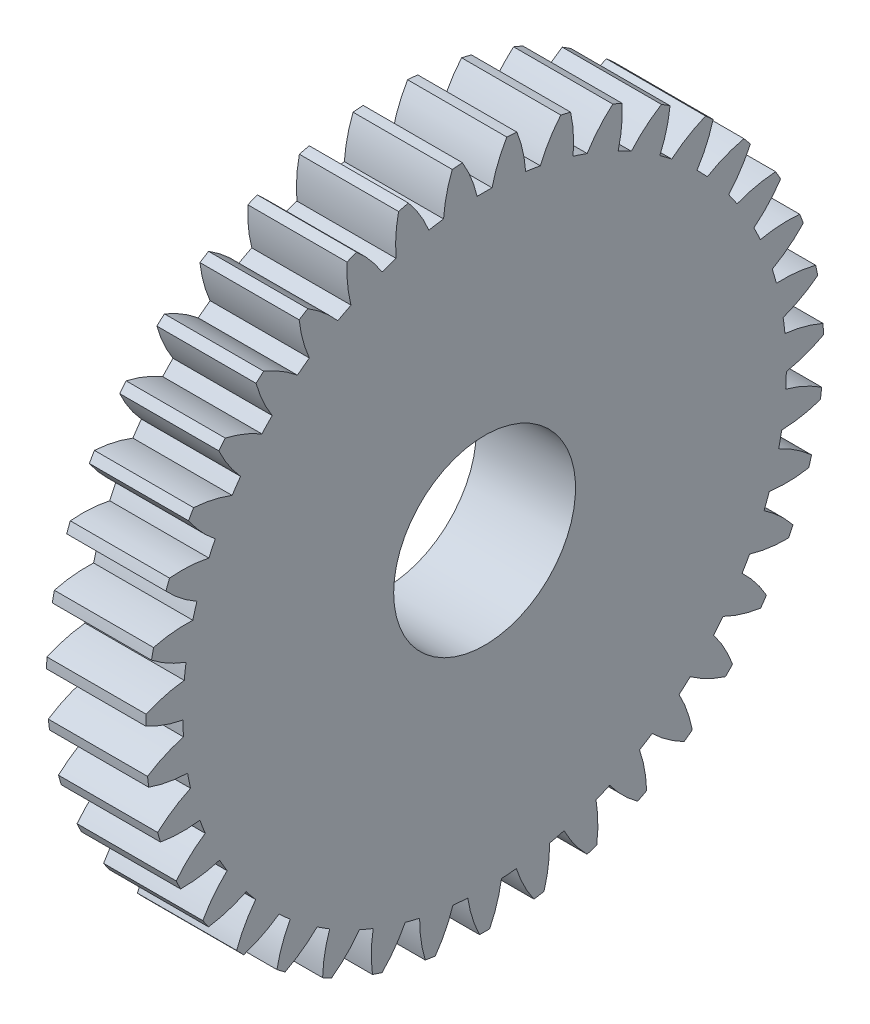
SolidWorks part; units mm, degrees
ref_plane "Plane1" through (0, 0, 0) normal (0, 0, 1) x (1, 0, 0)
ref_plane "Plane2" through (0, 0, 0) normal (0, 1, 0) x (1, 0, 0)
ref_plane "Plane3" through (0, 0, 0) normal (1, 0, 0) x (0, 0, -1)
other "Configuration Table"
sketch "HoldingSke" plane through (0, 0, 0) normal (0, 1, 0) x (1, 0, 0)
  line L0 (0, 0) -> (0.7771, -0.6293)
  line L1 (-15, 0) -> (100, 0) construction
  line L2 (0, 0) -> (-2.1039, 2.3779)
  line L3 (0, 0) -> (-11.863, 4.5341)
  line L4 (0, 0) -> (6.7114, 5.4348)
  line L5 (0, 0) -> (-46.8476, -17.4728)
  line L6 (0, 0) -> (-4.9738, -3.3558)
  line L7 (-2.1039, 2.3779) -> (8.6586, 51.2059)
  line L8 (-76.2, 54.61) -> (-74.4, 54.61)
  line L9 (-71.009, 38.7566) -> (-53.1078, 45.2721)
  line L10 (-76.2, 71.12) -> (104.1128, 71.12)
  line L11 (0, 0) -> (-6, 0)
  line L12 (-76.2, 101.6) -> (-76.162, 101.6)
  line L13 (24.9733, 27.94) -> (52.9518, 28.4284)
  line L14 (24.9733, 27.94) -> (24.9743, 27.94)
  line L15 (24.9733, 27.94) -> (100.4006, 29.5858)
  line L16 (-63.627, -1) -> (-12.827, -1)
  circle A0 centre (0, 0) radius 5.5
  circle A1 centre (0, 0) radius 18.249
  circle A2 centre (0, 0) radius 37.5
  circle A3 centre (0, 0) radius 5.5
  dimension "MHD" = 36.498
  dimension "Hub_dia" = 75
  dimension "Bore" = 11
  dimension "MBD" = 11
  dimension "Num_teeth" = 39
  dimension "Pitch" = 1
  dimension "Overall_len" = 50
  dimension "Show_teeth" = 39
  dimension "Thickness" = 6
  dimension "OAL" = 50.0001
  dimension "T_dim" = 1.8
  dimension "Ap" = 20
  dimension "H" = 19.05
  dimension "Pitch_radius" = 180.3128
  dimension "Width" = 6
  dimension "Backlash" = 0.038
  dimension "Addendum_fac" = 1
  dimension "Dedendum_fac" = 1.25
  dimension "Clearance_fac" = 0.25
  dimension "Dedendum_add" = 0.001
  dimension "Module" = 1
sketch "BasProSke" plane through (0, 0, 0) normal (0, 1, 0) x (1, 0, 0)
  line L0 (-10, 0) -> (60, 0) construction
  line L1 (0, 0) -> (0, 20.5)
  line L2 (0, 0) -> (6, 0)
  line L3 (6, 0) -> (6, 20.5)
  line L4 (6, 20.5) -> (0, 20.5)
  dimension "Thickness" = 6
  dimension "Diameter" = 41
revolve "Base-Revolve" add sketch "BasProSke" angle 360 about L0
sketch "TooCutSke" plane through (0, 0, 0) normal (1, 0, 0) x (0, 0, -1)
  line L1 (0, 0) -> (0, 107) construction
  line L2 (0, 0) -> (-0.8517, 19.4814) construction
  line L3 (0, 0) -> (-3.1361, 38.8471) construction
  line L4 (-0.8517, 19.4814) -> (-1.568, 19.4236) construction
  arc A0 (0.4501, 18.2434) -> (-0.4501, 18.2434) centre (0, 0) ccw
  arc A1 (1.358, 20.4804) -> (-1.358, 20.4804) centre (0, 0) ccw
  circle A2 centre (0, 0) radius 19.5 construction
  circle A3 centre (0, 0) radius 18.324 construction
  arc A4 (-0.4501, 18.2434) -> (-1.358, 20.4804) centre (-8.0443, 16.4638) ccw
  arc A5 (1.358, 20.4804) -> (0.4501, 18.2434) centre (8.0443, 16.4638) ccw
  dimension "Root_dia" = 36.498
  dimension "Overcut_dia" = 41.0508
  dimension "Pitch_dia" = 39
  dimension "Base_dia" = 36.648
  dimension "Flank_rad" = 7.8
  dimension "Half_ang" = 4.615
  dimension "Half_CT" = 0.7187
extrude "ToothCut" cut sketch "TooCutSke" along normal through all
fillet "Breaks" [suppressed] radius 0.02
fillet "RootFillets" [suppressed] radius 0.251
pattern_circular "TeethCuts" count 39 every 9.231 about axis through (-10, 0, 0) along (1, 0, 0) of "ToothCut", "RootFillets", "Breaks"
sketch "HubNeaOneSke" plane through (0, 0, 0) normal (-1, 0, 0) x (0, 0, 1)
  circle A0 centre (0, 0) radius 18.249
  dimension "Diameter" = 36.498
extrude "HubNearOne" [suppressed] add sketch "HubNeaOneSke" along normal blind 44.0001
sketch "HubNeaBotSke" plane through (0, 0, 0) normal (-1, 0, 0) x (0, 0, 1)
  circle A0 centre (0, 0) radius 18.249
  dimension "Diameter" = 36.498
extrude "HubNearBoth" [suppressed] add sketch "HubNeaBotSke" along normal blind 22
ref_plane "FarPln" through (6, 0, 0) normal (1, 0, 0) x (0, 0, -1)
sketch "HubFarSke" plane through (6, 0, 0) normal (1, 0, 0) x (0, 0, -1)
  circle A0 centre (0, 0) radius 18.249
  dimension "Diameter" = 36.498
extrude "HubFar" [suppressed] add sketch "HubFarSke" along normal blind 22
sketch "BorSke" plane through (0, 0, 0) normal (1, 0, 0) x (0, 0, -1)
  circle A0 centre (0, 0) radius 5.5
  dimension "Diameter" = 11
extrude "Bore" cut sketch "BorSke" along normal mid plane 100.0001
sketch "KeySke" plane through (0, 0, 0) normal (1, 0, 0) x (0, 0, -1)
  line L0 (-2, 0) -> (-2, 7.3)
  line L1 (-2, 7.3) -> (2, 7.3)
  line L2 (2, 7.3) -> (2, 0)
  line L3 (0, 0) -> (0, 34) construction
  line L4 (-2, 0) -> (2, 0)
  dimension "Offset" = 7.3
  dimension "Width" = 4
extrude "Keyway" [suppressed] cut sketch "KeySke" along normal mid plane 100.0001
pattern_circular "Keyway2" [suppressed] count 2 every 90 about axis through (-10, 0, 0) along (1, 0, 0)
equation "' \"Module@HoldingSke\" = 6.35"
equation "' \"Num_teeth@HoldingSke\" = 12"
equation "' \"Ap@HoldingSke\" =  20"
equation "' \"Ap@HoldingSke\" = 20"
equation "' \"Width@HoldingSke\" = 0.5 * 25.4"
equation "' \"Hub_dia@HoldingSke\"= 1 * 25.4"
equation "' \"Hub_dia@HoldingSke\" = 1 * 25.4"
equation "' \"Overall_len@HoldingSke\" = 1.0 * 25.4"
equation "' \"Bore@HoldingSke\" = 0.75 * 25.4"
equation "' \"T_dim@HoldingSke\" = 0.1 * 25.4"
equation "' \"Width@KeySke\" = 0.25 * 25.4"
equation "' \"Show_teeth@HoldingSke\" = 13"
equation "' \"Backlash@HoldingSke\" = 0.009 * 25.4"
equation "' \"Addendum_fac@HoldingSke\" = 1.0"
equation "' \"Dedendum_fac@HoldingSke\" = 1.25"
equation "' \"Dedendum_add@HoldingSke\" = 0.00005 * 25.4"
equation "' \"Clearance_fac@HoldingSke\" = 0.25"
equation "\"Pitch@HoldingSke\" = 1 / \"Module@HoldingSke\""
equation "\"Overcut_dia@TooCutSke\" = (\"Num_teeth@HoldingSke\" + 2 * \"Addendum_fac@HoldingSke\") / \"Pitch@HoldingSke\" + 0.002 * 25.4"
equation "\"Pitch_dia@TooCutSke\" = \"Num_teeth@HoldingSke\" / \"Pitch@HoldingSke\""
equation "\"Base_dia@TooCutSke\" = \"Num_teeth@HoldingSke\" / \"Pitch@HoldingSke\" * cos((\"Ap@HoldingSke\"  * 3.14159265 / 180))"
equation "\"Root_dia@TooCutSke\" = (\"Num_teeth@HoldingSke\" + 2) / \"Pitch@HoldingSke\" - 2 * (\"Addendum_fac@HoldingSke\" + \"Dedendum_fac@HoldingSke\") / \"Pitch@HoldingSke\" - \"Dedendum_add@HoldingSke\" * 2"
equation "\"Half_ang@TooCutSke\" = 180 / \"Num_teeth@HoldingSke\""
equation "\"Half_CT@TooCutSke\" = \"Num_teeth@HoldingSke\" / \"Pitch@HoldingSke\" * sin((3.14159265 / 2 / \"Num_teeth@HoldingSke\")) / 2 - 7 * \"Backlash@HoldingSke\" / 4"
equation "\"Flank_rad@TooCutSke\" = \"Num_teeth@HoldingSke\" / \"Pitch@HoldingSke\" / 5"
equation "\"Radius@RootFillets\" = \"Clearance_fac@HoldingSke\" / \"Pitch@HoldingSke\" + \"Dedendum_add@HoldingSke\""
equation "\"Break_rad@Breaks\" = 0.02 / \"Pitch@HoldingSke\""
equation "\"Thickness@HoldingSke\" = \"Width@HoldingSke\""
equation "\"OAL@HoldingSke\" = \"Thickness@HoldingSke\""
equation "\"MHD@HoldingSke\" = (\"Num_teeth@HoldingSke\" + 2) / \"Pitch@HoldingSke\" - 2 * (\"Addendum_fac@HoldingSke\" + \"Dedendum_fac@HoldingSke\")  / \"Pitch@HoldingSke\" - \"Dedendum_add@HoldingSke\" * 2"
equation "\"MBD@HoldingSke\" = (\"Num_teeth@HoldingSke\" + 2) / \"Pitch@HoldingSke\" - 2 * (\"Addendum_fac@HoldingSke\" + \"Dedendum_fac@HoldingSke\")  / \"Pitch@HoldingSke\" - \"Dedendum_add@HoldingSke\" * 2 - 0.002 * 25.4"
equation "\"MHD@HoldingSke\" = ((sgn( \"MHD@HoldingSke\" - \"Hub_dia@HoldingSke\" )-1)*( \"MHD@HoldingSke\" - \"Hub_dia@HoldingSke\" ))/-2+ \"Hub_dia@HoldingSke\""
equation "\"MBD@HoldingSke\" = ((sgn( \"MBD@HoldingSke\" - \"Bore@HoldingSke\" )-1)*( \"MBD@HoldingSke\" - \"Bore@HoldingSke\" ))/-2+ \"Bore@HoldingSke\""
equation "\"OAL@HoldingSke\" = ((sgn( \"OAL@HoldingSke\" - \"Overall_len@HoldingSke\" )+1)*( \"OAL@HoldingSke\" - \"Overall_len@HoldingSke\" ))/2 + \"Overall_len@HoldingSke\" + 0.000002 * 25.4"
equation "\"Num_teeth@TeethCuts\" = int( \"Show_teeth@HoldingSke\" ) + 1"
equation "\"Num_teeth@TeethCuts\" = ((sgn( \"Num_teeth@TeethCuts\" - \"Num_teeth@HoldingSke\" )-1)*( \"Num_teeth@TeethCuts\" - \"Num_teeth@HoldingSke\" ))/-2+ \"Num_teeth@HoldingSke\""
equation "\"Num_teeth@TeethCuts\" = ((sgn( \"Num_teeth@TeethCuts\" - 2.0)+1)*( \"Num_teeth@TeethCuts\" - 2.0))/2 +2.0"
equation "\"Angle@TeethCuts\" = 360.0 / \"Num_teeth@HoldingSke\""
equation "\"Diameter@BasProSke\" = (\"Num_teeth@HoldingSke\" + 2 * \"Addendum_fac@HoldingSke\") / \"Pitch@HoldingSke\""
equation "\"Thickness@BasProSke\"  = \"Thickness@HoldingSke\""
equation "' \"Fillet_rad@BasProSke\" =  \"Thickness@HoldingSke\" * 0.05"
equation "' \"Fillet_rad@BasProSke\" = \"Thickness@HoldingSke\" * 0.05"
equation "\"MHD@HoldingSke\" = ((sgn( \"MHD@HoldingSke\" - \"Root_dia@TooCutSke\" )-1)*( \"MHD@HoldingSke\" - \"Root_dia@TooCutSke\" ))/-2+ \"Root_dia@TooCutSke\""
equation "\"Diameter@HubNeaOneSke\" = \"MHD@HoldingSke\""
equation "\"Length@HubNearOne\" = \"OAL@HoldingSke\" - \"Thickness@BasProSke\""
equation "\"Diameter@HubNeaBotSke\" = \"MHD@HoldingSke\""
equation "\"Length@HubNearBoth\" = ( \"OAL@HoldingSke\" - \"Thickness@BasProSke\" ) / 2.0"
equation "\"Thickness@FarPln\" = \"Thickness@BasProSke\""
equation "\"Diameter@HubFarSke\" = \"MHD@HoldingSke\""
equation "\"Length@HubFar\" = ( \"OAL@HoldingSke\" - \"Thickness@BasProSke\" ) / 2.0"
equation "\"Diameter@BorSke\" = \"MBD@HoldingSke\""
equation "\"D1@Bore\" = \"OAL@HoldingSke\" * 2.0"
equation "\"D1@Keyway\" = \"OAL@HoldingSke\" * 2.0"
equation "\"Offset@KeySke\" = \"T_dim@HoldingSke\" + \"MBD@HoldingSke\" / 2.0"
